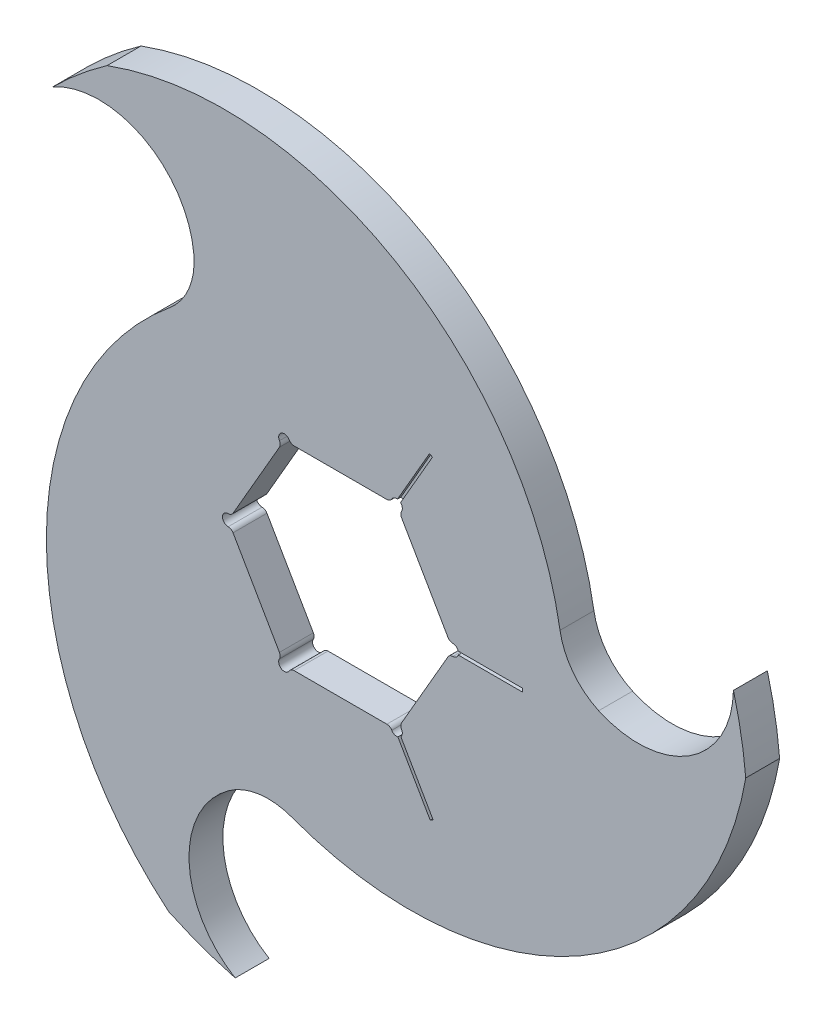
SolidWorks part; units mm, degrees
ref_plane "Front Plane" through (0, 0, 0) normal (0, 0, 1) x (1, 0, 0)
ref_plane "Top Plane" through (0, 0, 0) normal (0, 1, 0) x (1, 0, 0)
ref_plane "Right Plane" through (0, 0, 0) normal (1, 0, 0) x (0, 0, -1)
sketch "Sketch1" plane through (0, 0, 0) normal (0, 0, 1) x (1, 0, 0)
  line L6 (0, 0) -> (-14.35, 0) construction
  line L7 (0, 0) -> (33.0486, 0) construction
  line L8 (58.5677, 0) -> (63.1215, 0) construction
  line L9 (6.8416, 14.35) -> (8.285, 14.35) construction
  line L10 (-15.8483, -1.25) -> (-9.0067, -13.1)
  line L11 (-6.8416, -14.35) -> (6.8416, -14.35)
  line L12 (9.0067, -13.1) -> (15.8483, -1.25)
  line L13 (15.8483, 1.25) -> (9.0067, 13.1)
  line L14 (6.8416, 14.35) -> (-6.8416, 14.35)
  line L15 (-9.0067, 13.1) -> (-15.8483, 1.25)
  line L16 (8.285, 14.35) -> (9.0067, 13.1) construction
  line L17 (-16.57, 0) -> (-62.325, 0) construction
  arc A3 (-34.4264, 49.1408) -> (-42.4264, 42.4264) centre (0, 0) ccw
  arc A4 (-42.4264, 42.4264) -> (-22.6091, 24.8474) centre (-35.6099, 30.151) cw
  arc A5 (59.7704, 5.2438) -> (57.9555, 15.5291) centre (0, 0) ccw
  arc A6 (-10.2139, -32.0037) -> (59.7704, 5.2438) centre (10.2954, 13.8318) ccw
  arc A7 (57.9555, 15.5291) -> (32.823, 7.1564) centre (43.9165, 15.7636) cw
  arc A8 (-25.344, -54.3846) -> (-15.5291, -57.9555) centre (0, 0) ccw
  arc A9 (-22.6091, 24.8474) -> (-25.344, -54.3846) centre (6.8309, -15.832) ccw
  arc A10 (-15.5291, -57.9555) -> (-10.2139, -32.0037) centre (-8.3066, -45.9146) cw
  arc A11 (32.823, 7.1564) -> (-34.4264, 49.1408) centre (-17.1264, 2.0002) ccw
  circle A12 centre (0, 0) radius 60 construction
  circle A13 centre (0, 0) radius 14.35 construction
  arc A14 (9.0067, 13.9333) -> (7.5633, 14.7667) centre (8.285, 14.35) ccw
  arc A15 (9.0067, 13.1) -> (9.0067, 13.9333) centre (9.7284, 13.5167) cw
  arc A16 (7.5633, 14.7667) -> (6.8416, 14.35) centre (6.8416, 15.1833) cw
  arc A17 (16.57, 0.8333) -> (15.8483, 1.25) centre (16.57, 1.6667) cw
  arc A18 (16.57, -0.8333) -> (16.57, 0.8333) centre (16.57, 0) ccw
  arc A19 (15.8483, -1.25) -> (16.57, -0.8333) centre (16.57, -1.6667) cw
  arc A20 (9.0067, -13.9333) -> (9.0067, -13.1) centre (9.7284, -13.5167) cw
  arc A21 (7.5633, -14.7667) -> (9.0067, -13.9333) centre (8.285, -14.35) ccw
  arc A22 (6.8416, -14.35) -> (7.5633, -14.7667) centre (6.8416, -15.1833) cw
  arc A23 (-7.5633, -14.7667) -> (-6.8416, -14.35) centre (-6.8416, -15.1833) cw
  arc A24 (-9.0067, -13.9333) -> (-7.5633, -14.7667) centre (-8.285, -14.35) ccw
  arc A25 (-9.0067, -13.1) -> (-9.0067, -13.9333) centre (-9.7284, -13.5167) cw
  arc A26 (-16.57, -0.8333) -> (-15.8483, -1.25) centre (-16.57, -1.6667) cw
  arc A27 (-16.57, 0.8333) -> (-16.57, -0.8333) centre (-16.57, 0) ccw
  arc A28 (-15.8483, 1.25) -> (-16.57, 0.8333) centre (-16.57, 1.6667) cw
  arc A29 (-9.0067, 13.9333) -> (-9.0067, 13.1) centre (-9.7284, 13.5167) cw
  arc A30 (-7.5633, 14.7667) -> (-9.0067, 13.9333) centre (-8.285, 14.35) ccw
  arc A31 (-6.8416, 14.35) -> (-7.5633, 14.7667) centre (-6.8416, 15.1833) cw
  point P32 (0, 0)
  point P74 (0, 0)
  dimension "D1" = 28.7
  dimension "D5" = 6
  dimension "D2" = 1.6667
  dimension "D3" = 0.8333
extrude "Boss-Extrude1" add sketch "Sketch1" along normal mid plane 5
fillet "Fillet1" radius 10 3 edges at (-10.2139, -32.0037, 0) (32.823, 7.1564, 0) (-22.6091, 24.8474, 0)
sketch "Sketch2" plane through (0, 0, 2.5) normal (0, 0, 1) x (1, 0, 0)
  line L0 (0, 0) -> (8.7016, -15.0717) construction
  line L6 (8.6681, -14.5137) -> (13.6681, -23.1739)
  line L22 (8.7016, -15.0717) -> (8.4516, -14.6387) construction
  line L23 (16.834, -0.2503) -> (16.834, 0.2497)
  line L24 (8.2351, -14.7637) -> (8.6681, -14.5137)
  line L25 (8.2351, -14.7637) -> (13.2351, -23.4239)
  line L26 (13.2351, -23.4239) -> (13.6681, -23.1739)
  line L31 (16.834, -0.2503) -> (26.834, -0.25)
  line L32 (16.834, 0.2497) -> (26.834, 0.25)
  line L33 (26.834, -0.25) -> (26.834, 0.25)
  line L34 (8.5641, 14.453) -> (8.131, 14.703)
  line L35 (8.5641, 14.453) -> (13.5636, 23.1135)
  line L36 (8.131, 14.703) -> (13.1305, 23.3635)
  line L37 (13.5636, 23.1135) -> (13.1305, 23.3635)
  arc A0 (7.5633, -14.7667) -> (9.0067, -13.9333) centre (8.285, -14.35) ccw construction
  point P9 (8.4516, -14.6387)
  point P18 (0, 0)
  point P23 (-0.0339, -0.0604)
  dimension "D1" = 0.5
  dimension "D2" = 0.5
  dimension "D3" = 10
  dimension "D4" = 3
extrude "Cut-Extrude1" cut sketch "Sketch2" against normal blind 0.5
